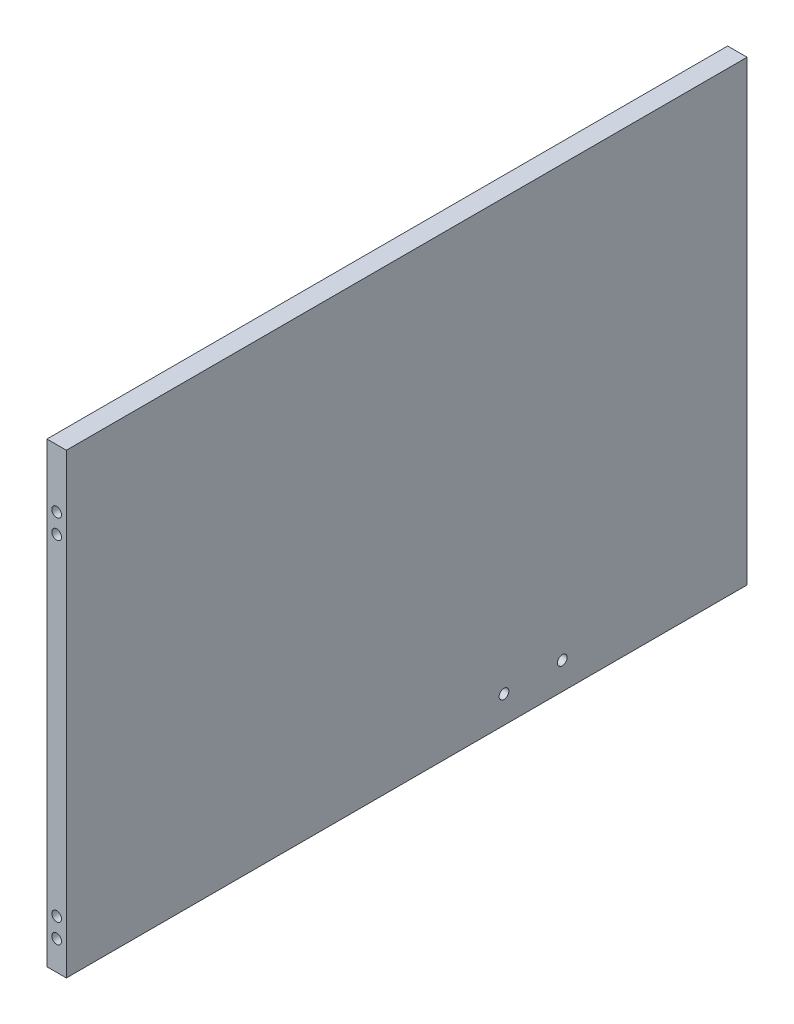
SolidWorks part; units mm, degrees
ref_plane "Front Plane" through (0, 0, 0) normal (0, 0, 1) x (1, 0, 0)
ref_plane "Top Plane" through (0, 0, 0) normal (0, 1, 0) x (1, 0, 0)
ref_plane "Right Plane" through (0, 0, 0) normal (1, 0, 0) x (0, 0, -1)
sketch "Sketch1" plane through (0, 0, 0) normal (1, 0, 0) x (0, 0, -1)
  line L1 (-175, 117.5) -> (175, 117.5)
  line L2 (-175, 117.5) -> (-175, -117.5)
  line L3 (-175, -117.5) -> (175, -117.5)
  line L4 (175, 117.5) -> (175, -117.5)
  line L5 (-175, 117.5) -> (175, -117.5) construction
  line L6 (-175, -117.5) -> (175, 117.5) construction
  point P0 (0, 0)
  dimension "D1" = 350
  dimension "D2" = 235
extrude "Boss-Extrude1" add sketch "Sketch1" along normal blind 10
sketch "Sketch2" plane through (10, 0, 0) normal (1, 0, 0) x (0, 0, -1)
  line L0 (-175, -117.5) -> (175, -117.5) construction
  line L1 (175, -117.5) -> (175, 117.5) construction
  circle A0 centre (50, -103.5) radius 2.5
  circle A1 centre (80, -103.5) radius 2.5
  dimension "D2" = 5
  dimension "D1" = 30
  dimension "D3" = 14
  dimension "D4" = 95
extrude "Cut-Extrude1" cut sketch "Sketch2" against normal through all
sketch "Sketch3" plane through (0, 0, -175) normal (0, 0, -1) x (-1, 0, 0)
  line L0 (-10, 117.5) -> (0, 117.5) construction
  line L1 (-10, -117.5) -> (0, -117.5) construction
  line L2 (0, -117.5) -> (0, 117.5) construction
  circle A0 centre (-5, 87.5) radius 2.5
  circle A1 centre (-5, 77.5) radius 2.5
  circle A2 centre (-5, -92.5) radius 2.5
  circle A3 centre (-5, -102.5) radius 2.5
  dimension "D6" = 5
  dimension "D1" = 30
  dimension "D2" = 10
  dimension "D3" = 10
  dimension "D4" = 15
  dimension "D5" = 5
extrude "Cut-Extrude2" cut sketch "Sketch3" against normal blind 10
mirror "Mirror1" about plane through (0, 0, 0) normal (0, 0, 1) of "Cut-Extrude2"
